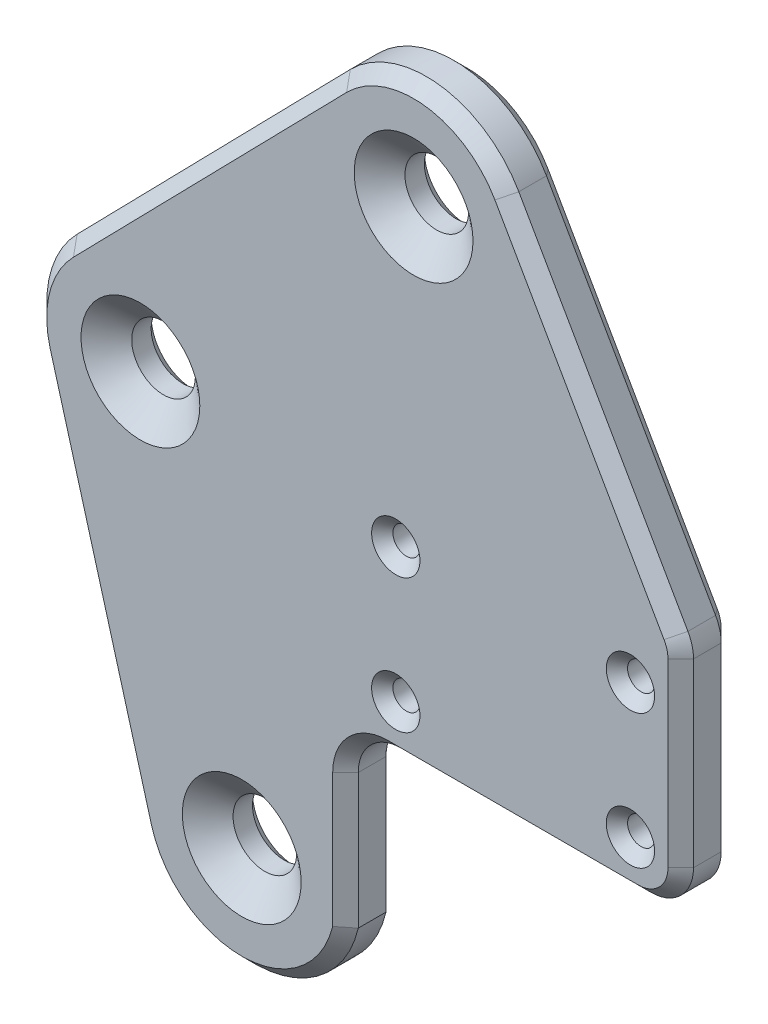
SolidWorks part; units mm, degrees
material "PET"
ref_plane "Front Plane" through (0, 0, 0) normal (0, 0, 1) x (1, 0, 0)
ref_plane "Top Plane" through (0, 0, 0) normal (0, 1, 0) x (1, 0, 0)
ref_plane "Right Plane" through (0, 0, 0) normal (1, 0, 0) x (0, 0, -1)
sketch "Sketch2" plane through (0, 0, 49.9814) normal (0, 0, 1) x (1, 0, 0)
  line L0 (-88.5343, -220.6839) -> (-74.5343, -212.6839) construction
  line L1 (-71.5343, -209.6839) -> (-81.956, -191.4306)
  line L2 (-71.5343, -223.6839) -> (-91.5343, -223.6839)
  line L3 (-71.5343, -223.6839) -> (-71.5343, -209.6839)
  line L4 (-71.5343, -209.6839) -> (-91.5343, -209.6839)
  line L5 (-91.5343, -223.6839) -> (-91.5343, -209.6839)
  line L6 (-71.5343, -223.6839) -> (-91.5343, -209.6839) construction
  line L7 (-71.5343, -209.6839) -> (-91.5343, -223.6839) construction
  line L8 (-92.0102, -190.1391) -> (-108.3079, -206.8031)
  line L9 (-109.8832, -212.9546) -> (-103.8379, -234.5533)
  line L10 (-91.5343, -223.6839) -> (-91.5343, -234.2645)
  circle A0 centre (-87.4705, -194.5791) radius 6.35
  circle A1 centre (-103.7682, -211.243) radius 6.35
  arc A2 (-91.5343, -231.419) -> (-91.5343, -234.2645) centre (-97.7229, -232.8418) ccw
  point P4 (-81.5343, -216.6839)
  dimension "D1" = 12.7
extrude "Boss-Extrude1" add sketch "Sketch2" along normal blind 3.175
hole_wizard "CSK for #6 Flat Head Machine Screw (100)1" positions "Sketch6" profile "Sketch7" countersink size "#6" standard "ANSI Inch" end condition through all
sketch "Sketch6" plane through (0, 0, 53.1564) normal (0, 0, 1) x (1, 0, 0)
  point P0 (-97.7229, -232.8418)
  point P3 (-87.4705, -194.5791)
  point P6 (-103.7682, -211.243)
sketch "Sketch7" plane through (-97.7229, -232.8418, 53.1564) normal (1, 0, 0) x (0, -1, 0)
  line L0 (0, 0) -> (0, 3.175)
  line L1 (0, 3.175) -> (2.5336, 3.175)
  line L2 (1.8986, 2.54) -> (1.8986, 1.38)
  line L3 (1.8986, 1.38) -> (3.5433, 0)
  line L5 (3.5433, 0) -> (0, 0)
  line L6 (-1.8986, 1.38) -> (-3.5433, 0) construction
  line L7 (2.5336, 3.175) -> (1.8986, 2.54)
  line L8 (-2.5337, 3.175) -> (-1.8987, 2.54) construction
  line L11 (0, -6.35) -> (0, 107.95) construction
  dimension "Thru Hole Dia." = 3.7973
  dimension "Thru Hole Depth" = 3.175
  dimension "Near C'Sink Dia." = 7.0866
  dimension "Near C'Sink Angle" = 100
  dimension "Far C'Sink Dia." = 5.0673
  dimension "Far C'Sink Angle" = 90
fillet "Fillet1" radius 2.54 3 edges at (-71.5343, -209.6839, 51.5689) (-91.5343, -223.6839, 51.5689) (-71.5343, -223.6839, 51.5689)
hole_wizard "#52 (0.0635) Diameter Hole1" positions "Sketch8" profile "Sketch9" hole size "#52" standard "ANSI Inch" end condition through all
sketch "Sketch8" plane through (0, 0, 53.1564) normal (0, 0, 1) x (1, 0, 0)
  circle A0 centre (-88.5343, -212.6839) radius 1.25 construction
  circle A1 centre (-88.5343, -220.6839) radius 1.25 construction
  circle A2 centre (-74.5343, -212.6839) radius 1.25 construction
  circle A3 centre (-74.5343, -220.6839) radius 1.25 construction
  point P0 (-88.5343, -212.6839)
  point P2 (-74.5343, -212.6839)
  point P4 (-74.5343, -220.6839)
  point P6 (-88.5343, -220.6839)
sketch "Sketch9" plane through (-88.5343, -212.6839, 53.1564) normal (1, 0, 0) x (0, -1, 0)
  line L0 (0, 0) -> (0, 3.175)
  line L1 (0, 3.175) -> (1.4414, 3.175)
  line L2 (0.8064, 2.54) -> (0.8064, 0.635)
  line L3 (0.8064, 0.635) -> (1.4414, 0)
  line L5 (1.4414, 0) -> (0, 0)
  line L6 (-0.8064, 0.635) -> (-1.4414, 0) construction
  line L7 (1.4414, 3.175) -> (0.8064, 2.54)
  line L8 (-1.4415, 3.175) -> (-0.8065, 2.54) construction
  line L11 (0, -6.35) -> (0, 107.95) construction
  dimension "Thru Hole Dia." = 1.6129
  dimension "Thru Hole Depth" = 3.175
  dimension "Near C'Sink Dia." = 2.8829
  dimension "Near C'Sink Angle" = 90
  dimension "Far C'Sink Dia." = 2.8829
  dimension "Far C'Sink Angle" = 90
chamfer "Chamfer4" distance 0.762 angle 45 24 edges at (-97.5739, -239.19, 49.9814) (-97.5739, -239.19, 53.1564) (-106.8606, -223.754, 49.9814) (-106.8606, -223.754, 53.1564) (-109.9197, -209.6678, 49.9814) (-109.9197, -209.6678, 53.1564) (-91.5343, -230.2442, 49.9814) (-91.5343, -230.2442, 53.1564) (-100.1591, -198.4711, 49.9814) (-100.1591, -198.4711, 53.1564) (-90.7904, -224.4279, 53.1564) (-90.7904, -224.4279, 49.9814) (-86.6614, -188.2809, 49.9814) (-86.6614, -188.2809, 53.1564) (-81.5343, -223.6839, 53.1564) (-81.5343, -223.6839, 49.9814) (-76.9123, -200.2646, 53.1564) (-76.9123, -200.2646, 49.9814) (-72.2783, -222.94, 53.1564) (-72.2783, -222.94, 49.9814) (-71.6193, -209.7065, 53.1564) (-71.6193, -209.7065, 49.9814) (-71.5343, -215.7509, 49.9814) (-71.5343, -215.7509, 53.1564)
